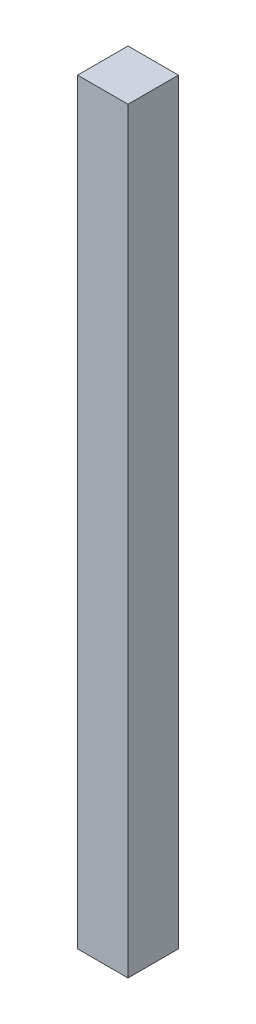
SolidWorks part; units mm, degrees
ref_plane "Ebene vorne" through (0, 0, 0) normal (0, 0, 1) x (1, 0, 0)
ref_plane "Ebene oben" through (0, 0, 0) normal (0, 1, 0) x (1, 0, 0)
ref_plane "Ebene rechts" through (0, 0, 0) normal (1, 0, 0) x (0, 0, -1)
sketch "Skizze2" plane through (0, 0, 0) normal (0, 1, 0) x (1, 0, 0)
  line L1 (-10, -10) -> (10, -10)
  line L2 (-10, -10) -> (-10, 10)
  line L3 (-10, 10) -> (10, 10)
  line L4 (10, -10) -> (10, 10)
  line L5 (-10, -10) -> (10, 10) construction
  line L6 (-10, 10) -> (10, -10) construction
  point P0 (0, 0)
  dimension "D1" = 20
  dimension "D2" = 20
extrude "Aufsatz-Linear austragen1" add sketch "Skizze2" along normal blind 300
